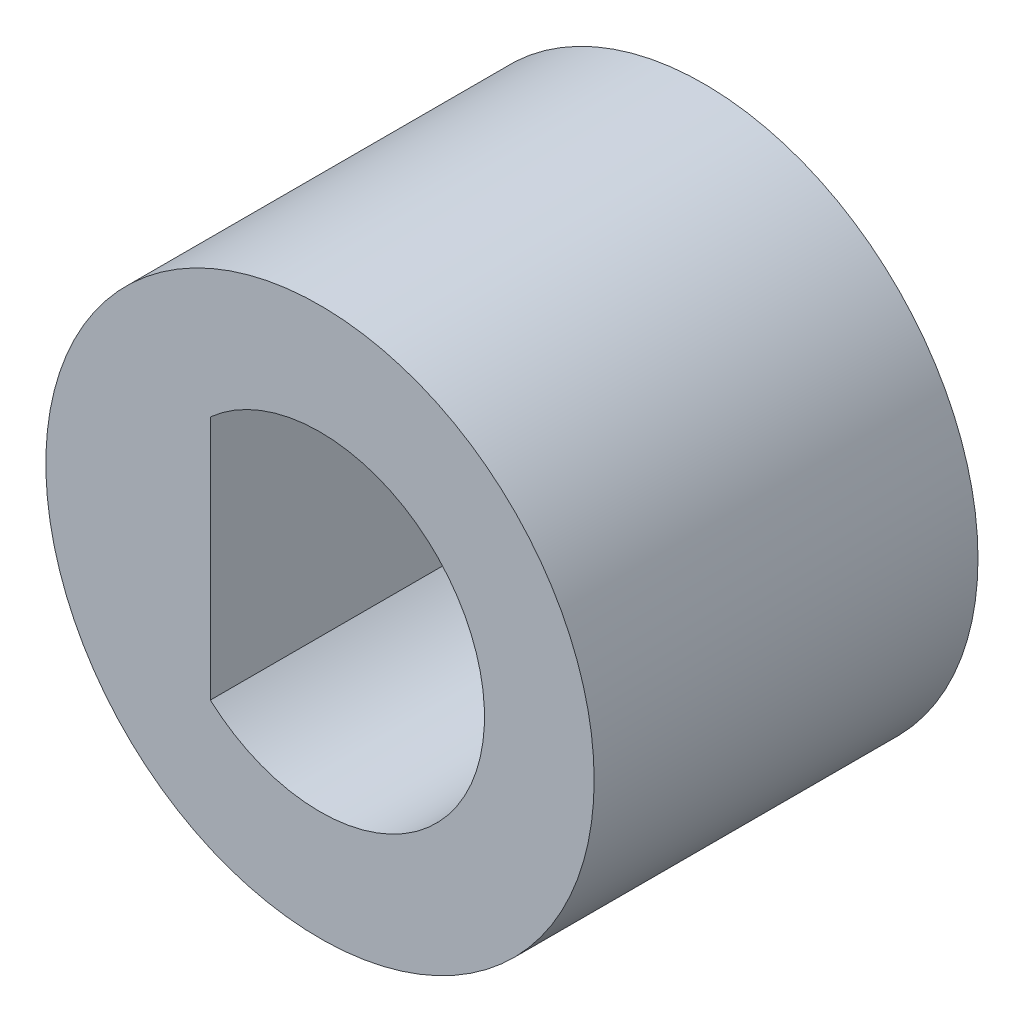
SolidWorks part; units mm, degrees
material "Brass"
ref_plane "Front Plane" through (0, 0, 0) normal (0, 0, 1) x (1, 0, 0)
ref_plane "Top Plane" through (0, 0, 0) normal (0, 1, 0) x (1, 0, 0)
ref_plane "Right Plane" through (0, 0, 0) normal (1, 0, 0) x (0, 0, -1)
sketch "Sketch1" plane through (0, 0, 0) normal (0, 0, 1) x (1, 0, 0)
  line L0 (-2, 2.2361) -> (-2, -2.2361)
  circle A0 centre (0, 0) radius 5
  circle A1 centre (0, 0) radius 3
  dimension "D1" = 10
  dimension "D2" = 6
  dimension "D3" = 2
extrude "Boss-Extrude1" add sketch "Sketch1" along normal blind 7 contours A0 A1 | L0 A1
